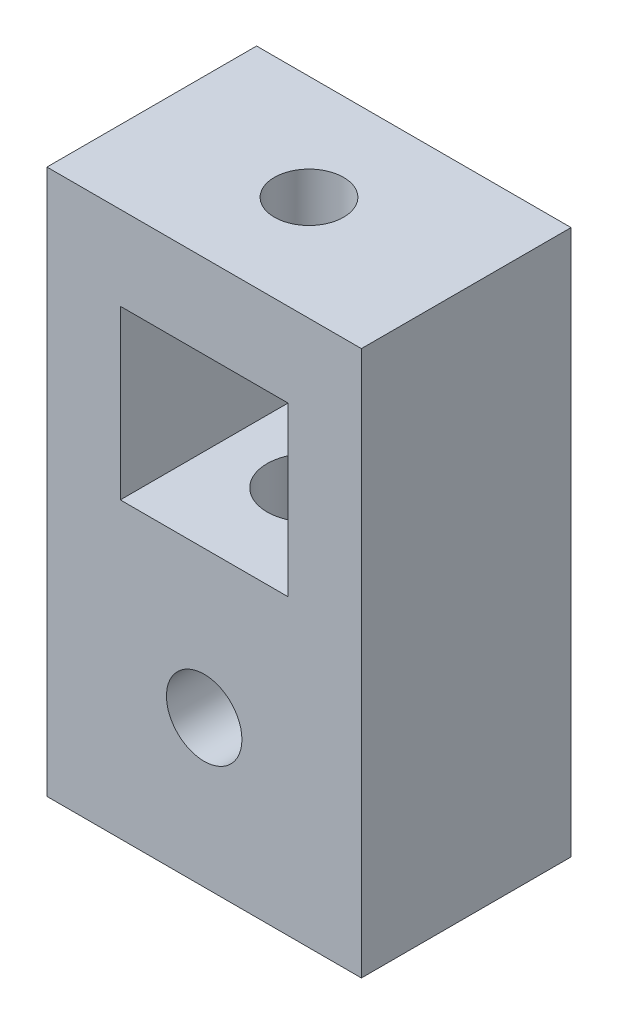
SolidWorks part; units mm, degrees
ref_plane "Front Plane" through (0, 0, 0) normal (0, 0, 1) x (1, 0, 0)
ref_plane "Top Plane" through (0, 0, 0) normal (0, 1, 0) x (1, 0, 0)
ref_plane "Right Plane" through (0, 0, 0) normal (1, 0, 0) x (0, 0, -1)
sketch "Sketch1" plane through (0, 0, 0) normal (0, 0, 1) x (1, 0, 0)
  line L1 (-8.0953, 9.9466) -> (6.9047, 9.9466)
  line L2 (-8.0953, 9.9466) -> (-8.0953, -4.0534)
  line L3 (-8.0953, -4.0534) -> (6.9047, -4.0534)
  line L4 (6.9047, 9.9466) -> (6.9047, -4.0534)
  dimension "D1" = 15
  dimension "D2" = 14
extrude "Boss-Extrude1" add sketch "Sketch1" along normal blind 10
sketch "Sketch2" plane through (0, 0, 10) normal (0, 0, 1) x (1, 0, 0)
  line L0 (-0.5953, -4.0534) -> (-0.5953, 9.9466) construction
  line L1 (-8.0953, -4.0534) -> (6.9047, -4.0534) construction
  line L2 (6.9047, 9.9466) -> (-8.0953, 9.9466) construction
  circle A0 centre (-0.5953, 2.9466) radius 1.8
  dimension "D1" = 3.6
  dimension "D2" = 7
extrude "Cut-Extrude1" cut sketch "Sketch2" against normal through all
sketch "Sketch3" plane through (0, 9.9466, 0) normal (0, 1, 0) x (1, 0, 0)
  line L0 (-8.0953, -5) -> (6.9047, -5) construction
  line L1 (-8.0953, -10) -> (-8.0953, 0) construction
  line L2 (6.9047, -10) -> (6.9047, 0) construction
  line L3 (-0.5953, -10) -> (-0.5953, 0) construction
  line L4 (6.9047, -10) -> (-8.0953, -10) construction
  line L5 (6.9047, 0) -> (-8.0953, 0) construction
  circle A0 centre (-0.5953, -5) radius 2
  dimension "D1" = 4
extrude "Cut-Extrude2" cut sketch "Sketch3" against normal blind 5
sketch "Sketch4" plane through (0, 9.9466, 0) normal (0, 1, 0) x (1, 0, 0)
  line L0 (6.9047, -10) -> (-8.0953, -10) construction
  line L1 (-8.0953, -10) -> (-4.5953, -10)
  line L2 (-8.0953, -10) -> (-8.0953, 0)
  line L3 (-8.0953, 0) -> (-4.5953, 0)
  line L4 (-4.5953, -10) -> (-4.5953, 0)
  line L5 (3.4047, -10) -> (6.9047, -10)
  line L6 (3.4047, -10) -> (3.4047, 0)
  line L7 (3.4047, 0) -> (6.9047, 0)
  line L8 (6.9047, -10) -> (6.9047, 0)
  line L9 (-8.0953, -10) -> (-8.0953, 0) construction
  line L11 (6.9047, 0) -> (-8.0953, 0) construction
  line L12 (6.9047, -10) -> (6.9047, 0) construction
  dimension "D1" = 3.5
extrude "Boss-Extrude2" add sketch "Sketch4" along normal blind 8
sketch "Sketch5" plane through (0, 17.9466, 0) normal (0, 1, 0) x (1, 0, 0)
  line L0 (-8.0953, -10) -> (-4.5953, -10) construction
  line L1 (-8.0953, -10) -> (6.9047, -10)
  line L2 (-8.0953, -10) -> (-8.0953, 0)
  line L3 (-8.0953, 0) -> (6.9047, 0)
  line L4 (6.9047, -10) -> (6.9047, 0)
  line L5 (-8.0953, 0) -> (-8.0953, -10) construction
  line L6 (-4.5953, 0) -> (-8.0953, 0) construction
  line L7 (6.9047, -10) -> (6.9047, 0) construction
extrude "Boss-Extrude3" add sketch "Sketch5" along normal blind 4
sketch "Sketch6" plane through (0, 21.9466, 0) normal (0, 1, 0) x (1, 0, 0)
  circle A0 centre (-0.5953, -5) radius 1.65
  circle A1 centre (-0.5953, -5) radius 2 construction
  dimension "D1" = 3.3
extrude "Cut-Extrude3" cut sketch "Sketch6" against normal up to surface (4 mm away) up to face at (-0.5953, 17.9466, 5)
